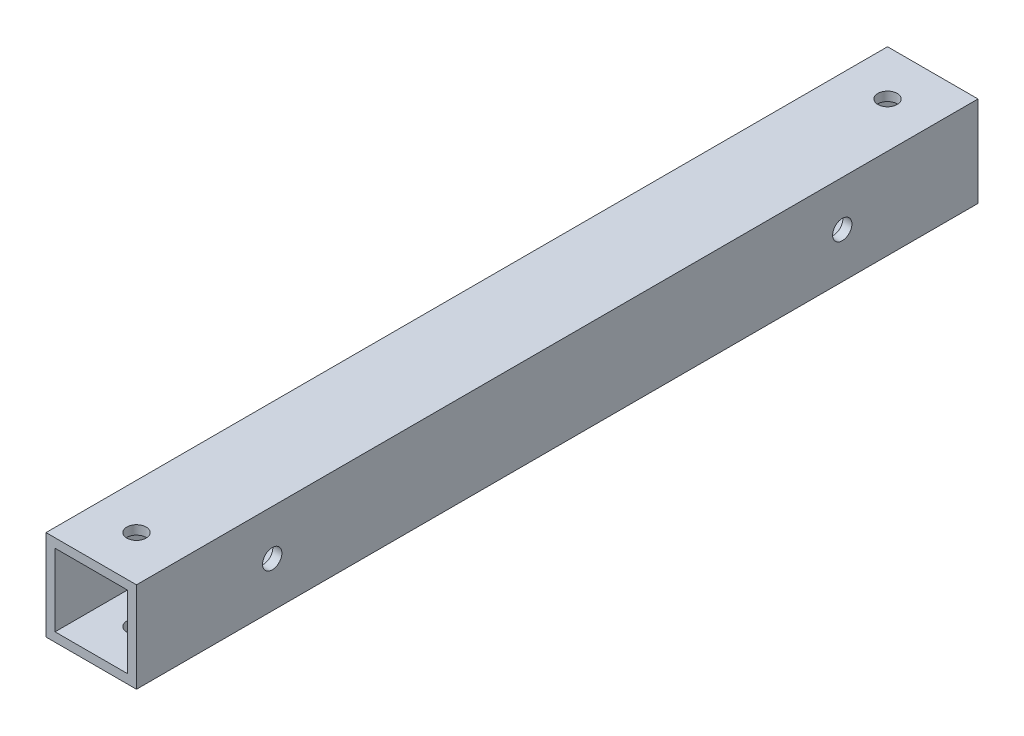
SolidWorks part; units mm, degrees
ref_plane "Front" through (0, 0, 0) normal (0, 0, 1) x (1, 0, 0)
ref_plane "Top" through (0, 0, 0) normal (0, 1, 0) x (1, 0, 0)
ref_plane "Right" through (0, 0, 0) normal (1, 0, 0) x (0, 0, -1)
sketch "ｽｹｯﾁ1" plane through (0, 0, 0) normal (0, 0, 1) x (1, 0, 0)
  line L0 (-6, 6) -> (6, 6)
  line L1 (-7.5, -7.5) -> (7.5, -7.5)
  line L2 (-7.5, -7.5) -> (-7.5, 7.5)
  line L3 (-7.5, 7.5) -> (7.5, 7.5)
  line L4 (7.5, -7.5) -> (7.5, 7.5)
  line L5 (0, 7.5) -> (0, -7.5) construction
  line L6 (-7.5, 0) -> (7.5, 0) construction
  line L7 (6, -6) -> (6, 6)
  line L8 (-6, -6) -> (6, -6)
  line L9 (-6, -6) -> (-6, 6)
  point P0 (0, 0)
  dimension "D1" = 15
  dimension "D2" = 15
  dimension "D3" = 1.5
extrude "ﾎﾞｽ - 押し出し1" add sketch "ｽｹｯﾁ1" along normal blind 139.5
sketch "ｽｹｯﾁ2" plane through (0, 7.5, 0) normal (0, 1, 0) x (1, 0, 0)
  line L0 (7.5, -139.5) -> (-7.5, -139.5) construction
  line L1 (7.5, 0) -> (-7.5, 0) construction
  line L2 (7.5, -139.5) -> (7.5, 0) construction
  circle A0 centre (0, -7.5) radius 1.6
  circle A1 centre (0, -132) radius 1.6
  dimension "D1" = 7.5
  dimension "D2" = 7.5
  dimension "D3" = 3.2
  dimension "D4" = 3.2
  dimension "D5" = 7.5
  dimension "D6" = 7.5
extrude "ｶｯﾄ - 押し出し1" cut sketch "ｽｹｯﾁ2" against normal through all
sketch "ｽｹｯﾁ3" plane through (7.5, 0, 0) normal (1, 0, 0) x (0, 0, -1)
  line L0 (-139.5, -7.5) -> (-139.5, 7.5) construction
  line L1 (0, -7.5) -> (0, 7.5) construction
  line L2 (-139.5, -7.5) -> (0, -7.5) construction
  circle A0 centre (-117, 0) radius 1.6
  circle A1 centre (-22.5, 0) radius 1.6
  dimension "D1" = 3.2
  dimension "D2" = 3.2
  dimension "D3" = 22.5
  dimension "D4" = 22.5
  dimension "D5" = 7.5
  dimension "D6" = 7.5
extrude "ｶｯﾄ - 押し出し2" cut sketch "ｽｹｯﾁ3" against normal through all
